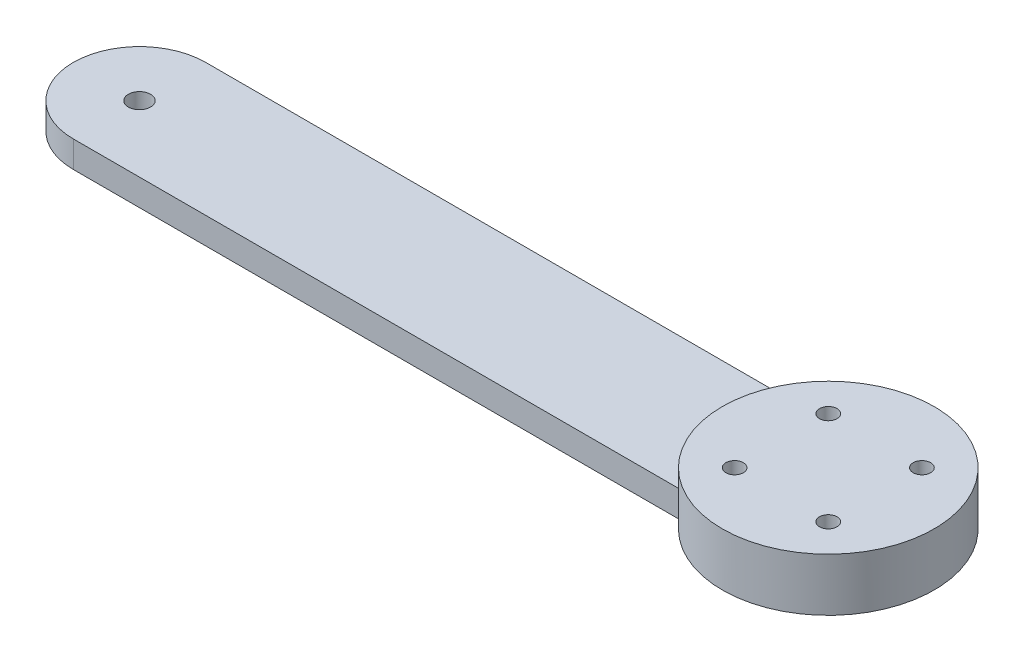
SolidWorks part; units mm, degrees
ref_plane "前视基准面" through (0, 0, 0) normal (0, 0, 1) x (1, 0, 0)
ref_plane "上视基准面" through (0, 0, 0) normal (0, 1, 0) x (1, 0, 0)
ref_plane "右视基准面" through (0, 0, 0) normal (1, 0, 0) x (0, 0, -1)
sketch "草图1" plane through (0, 0, 0) normal (0, 1, 0) x (1, 0, 0)
  line L0 (-65, 0) -> (65, 0) construction
  line L1 (-65, 12.5) -> (65, 12.5)
  line L2 (-65, -12.5) -> (65, -12.5)
  arc A0 (-65, 12.5) -> (-65, -12.5) centre (-65, 0) ccw
  arc A1 (65, -12.5) -> (65, 12.5) centre (65, 0) ccw
  point P2 (0, 0)
  dimension "D2" = 12.5
  dimension "D1" = 130
extrude "凸台-拉伸1" add sketch "草图1" along normal blind 5
sketch "草图7" plane through (0, 0, 0) normal (0, 1, 0) x (1, 0, 0)
  circle A0 centre (65, 0) radius 20
  dimension "D1" = 40
extrude "凸台-拉伸3" add sketch "草图7" along normal blind 10
sketch "草图8" plane through (0, 10, 0) normal (0, 1, 0) x (1, 0, 0)
  line L0 (65, 0) -> (56.1612, 8.8388) construction
  line L1 (52.5, 0) -> (65, 0) construction
  line L2 (65, 0) -> (56.1612, 8.8388) construction
  circle A5 centre (65, 0) radius 12.5 construction
  circle A6 centre (56.1612, 8.8388) radius 1.65
  circle A7 centre (73.8388, 8.8388) radius 1.65
  circle A8 centre (73.8388, -8.8388) radius 1.65
  circle A9 centre (56.1612, -8.8388) radius 1.65
  dimension "D1" = 25
  dimension "D2" = 45
  dimension "D3" = 3.3
  dimension "D4" = 4
extrude "切除-拉伸2" cut sketch "草图8" against normal up to next
sketch "草图9" plane through (0, 5, 0) normal (0, 1, 0) x (1, 0, 0)
  circle A0 centre (-65, 0) radius 2.1
  dimension "D1" = 4.2
extrude "切除-拉伸3" cut sketch "草图9" against normal up to next
